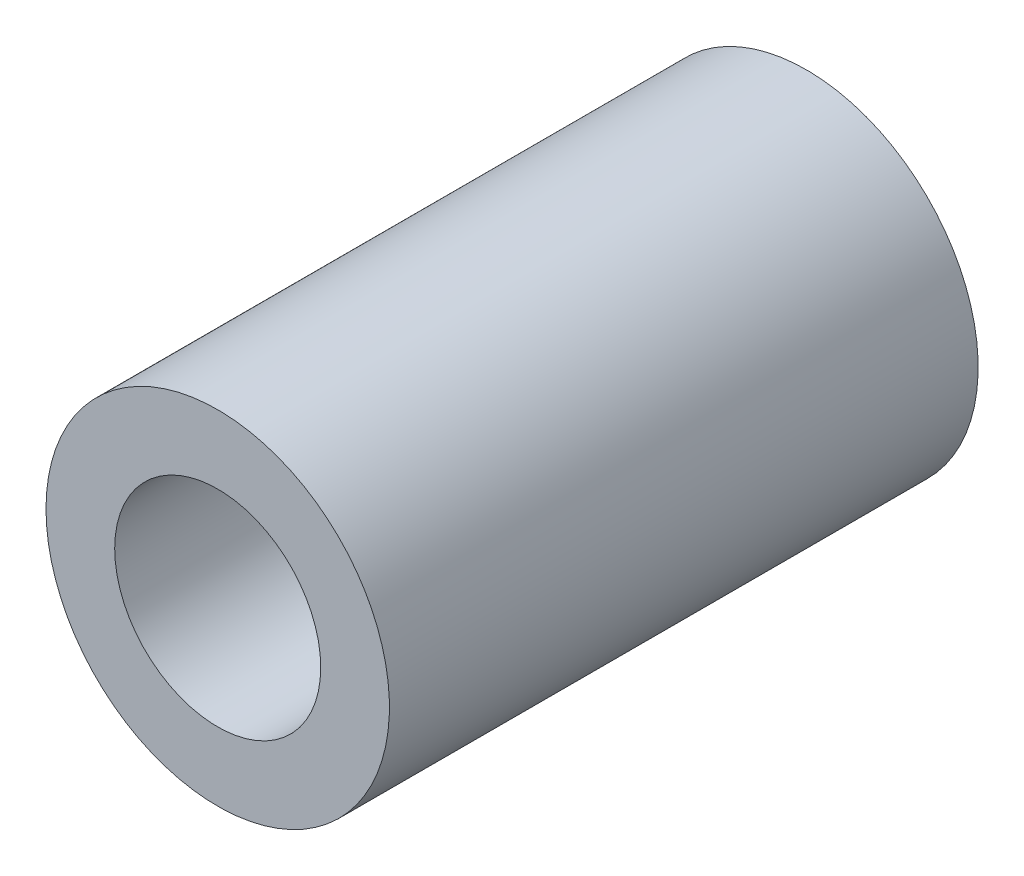
SolidWorks part; units mm, degrees
ref_plane "Front Plane" through (0, 0, 0) normal (0, 0, 1) x (1, 0, 0)
ref_plane "Top Plane" through (0, 0, 0) normal (0, 1, 0) x (1, 0, 0)
ref_plane "Right Plane" through (0, 0, 0) normal (1, 0, 0) x (0, 0, -1)
ref_plane "Plane1" through (0, 0, 0) normal (0, -1, 0) x (1, 0, 0)
sketch "Sketch1" plane through (0, 0, 0) normal (0, -1, 0) x (1, 0, 0)
  line L0 (7, 0) -> (7, 24)
  line L1 (7, 24) -> (4.2, 24)
  line L2 (4.2, 24) -> (4.2, 0)
  line L3 (4.2, 0) -> (7, 0)
  line L4 (0, 24) -> (0, 0) construction
revolve "Revolve1" add sketch "Sketch1" angle 360 about L4
